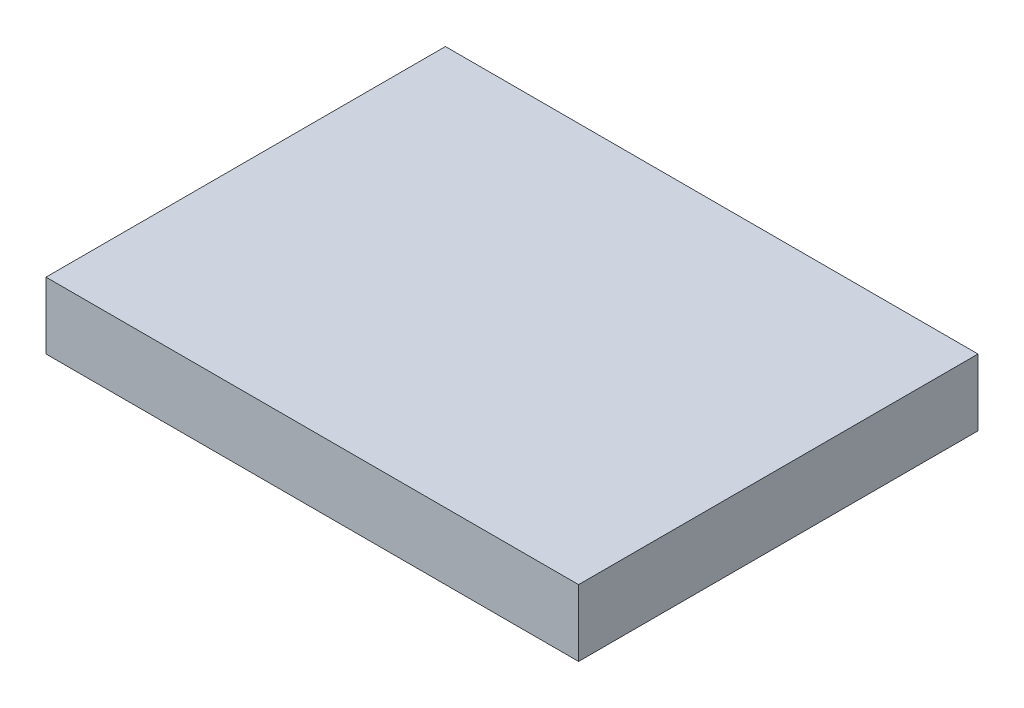
SolidWorks part; units mm, degrees
ref_plane "Front" through (0, 0, 0) normal (0, 0, 1) x (1, 0, 0)
ref_plane "Top" through (0, 0, 0) normal (0, 1, 0) x (1, 0, 0)
ref_plane "Right" through (0, 0, 0) normal (1, 0, 0) x (0, 0, -1)
sketch "Esboço1" plane through (0, 0, 0) normal (0, 1, 0) x (1, 0, 0)
  line L1 (-59.2816, 12.2003) -> (-35.2816, 12.2003)
  line L2 (-59.2816, 12.2003) -> (-59.2816, -5.7997)
  line L3 (-59.2816, -5.7997) -> (-35.2816, -5.7997)
  line L4 (-35.2816, 12.2003) -> (-35.2816, -5.7997)
  line L5 (-59.2816, 12.2003) -> (-35.2816, -5.7997) construction
  line L6 (-59.2816, -5.7997) -> (-35.2816, 12.2003) construction
  point P0 (-47.2816, 3.2003)
  dimension "D1" = 18
extrude "Ressalto-extrusão1" add sketch "Esboço1" along normal blind 3
